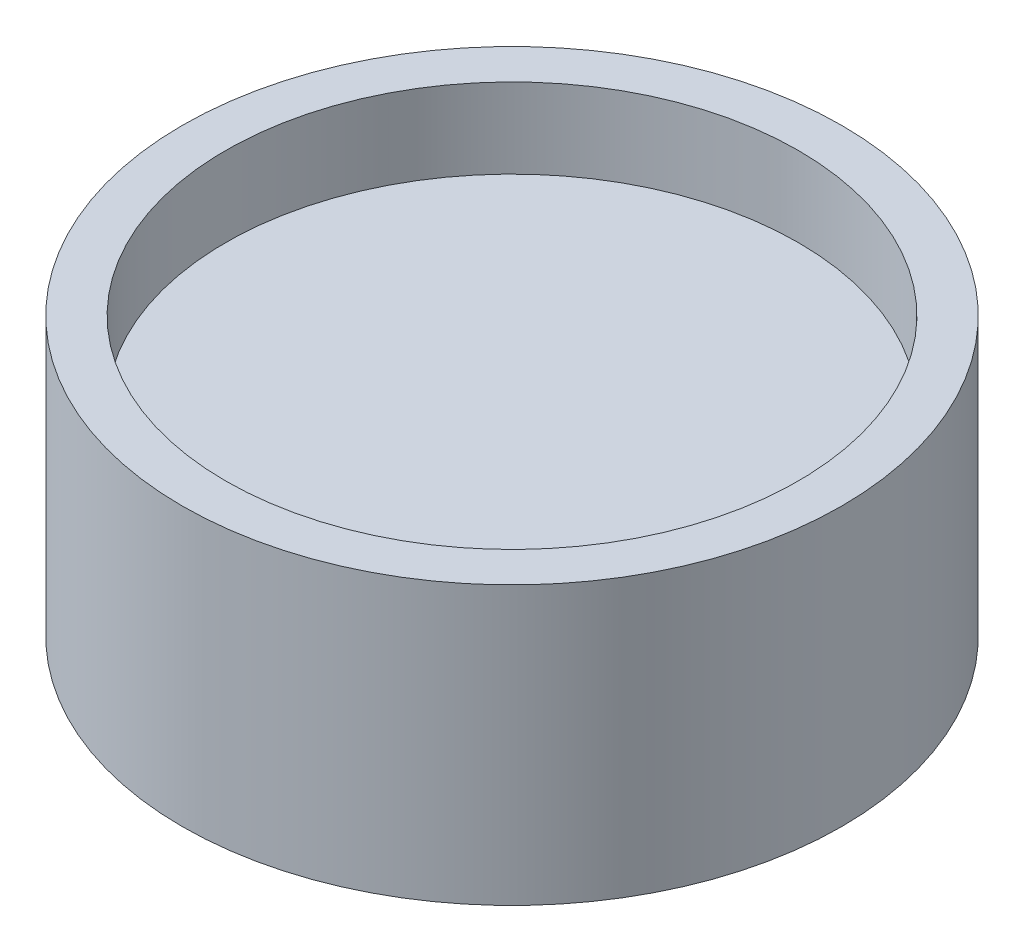
SolidWorks part; units mm, degrees
ref_plane "前视基准面" through (0, 0, 0) normal (0, 0, 1) x (1, 0, 0)
ref_plane "上视基准面" through (0, 0, 0) normal (0, 1, 0) x (1, 0, 0)
ref_plane "右视基准面" through (0, 0, 0) normal (1, 0, 0) x (0, 0, -1)
sketch "草图1" plane through (0, 0, 0) normal (0, 1, 0) x (1, 0, 0)
  circle A0 centre (0, 0) radius 19
extrude "凸台-拉伸1" add sketch "草图1" along normal blind 16 contours A0
sketch "草图2" plane through (0, 16, 0) normal (0, 1, 0) x (1, 0, 0)
  circle A0 centre (0, 0) radius 16.5
extrude "切除-拉伸1" cut sketch "草图2" against normal blind 4.6
sketch "草图3" plane through (0, 0, 0) normal (0, -1, 0) x (1, 0, 0)
  circle A0 centre (0, 0) radius 16.4
extrude "切除-拉伸2" cut sketch "草图3" against normal blind 4.6
